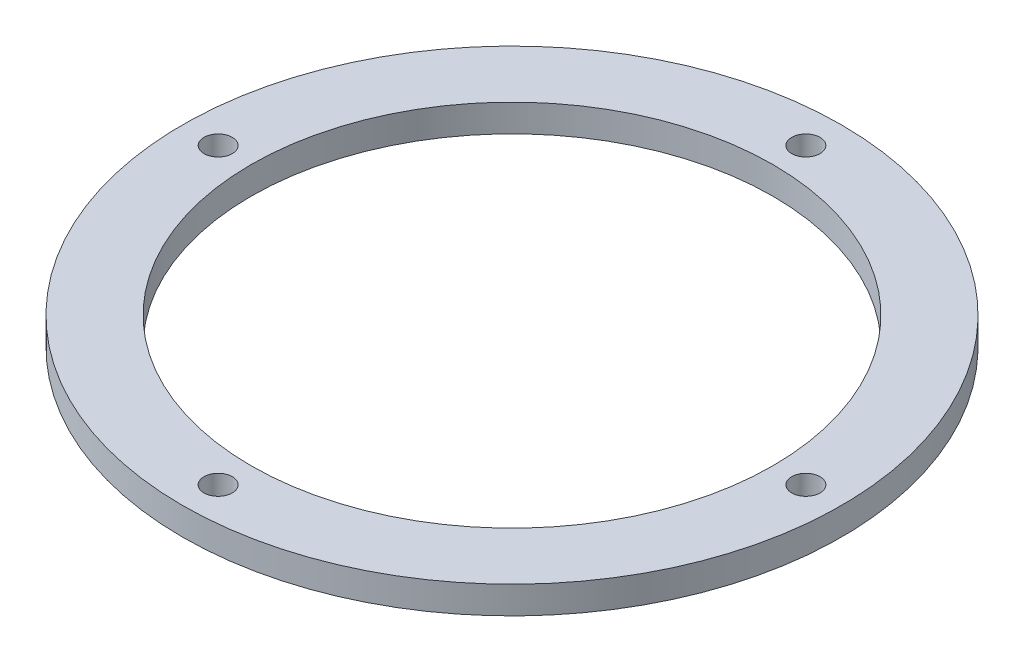
SolidWorks part; units mm, degrees
ref_plane "前视基准面" through (0, 0, 0) normal (0, 0, 1) x (1, 0, 0)
ref_plane "上视基准面" through (0, 0, 0) normal (0, 1, 0) x (1, 0, 0)
ref_plane "右视基准面" through (0, 0, 0) normal (1, 0, 0) x (0, 0, -1)
other "Configuration Table"
sketch "草图1" plane through (0, 0, 0) normal (0, 1, 0) x (1, 0, 0)
  circle A0 centre (0, 0) radius 60
  circle A1 centre (0, 0) radius 47.5
  dimension "D1" = 120
  dimension "D2" = 95
extrude "凸台-拉伸1" add sketch "草图1" along normal blind 5
sketch "草图2" plane through (0, 5, 0) normal (0, 1, 0) x (1, 0, 0)
  line L0 (0, 53.5) -> (0, 0) construction
  circle A0 centre (0, 53.5) radius 2.575
  circle A1 centre (53.5, 0) radius 2.575
  circle A2 centre (0, -53.5) radius 2.575
  circle A3 centre (-53.5, 0) radius 2.575
  point P13 (0, 0)
  dimension "D2" = 5.15
  dimension "D1" = 53.5
  dimension "D3" = 4
extrude "切除-拉伸1" cut sketch "草图2" against normal up to next
